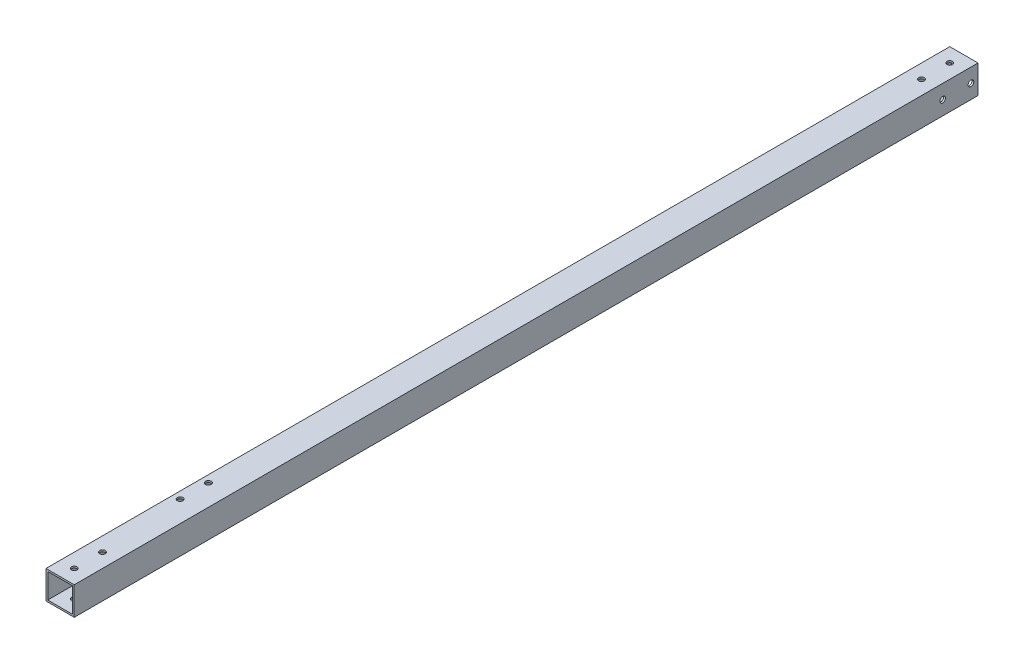
SolidWorks part; units mm, degrees
ref_plane "Front Plane" through (0, 0, 0) normal (0, 0, 1) x (1, 0, 0)
ref_plane "Top Plane" through (0, 0, 0) normal (0, 1, 0) x (1, 0, 0)
ref_plane "Right Plane" through (0, 0, 0) normal (1, 0, 0) x (0, 0, -1)
sketch "Sketch1" plane through (0, 0, 0) normal (0, 0, 1) x (1, 0, 0)
  line L1 (0, 0) -> (25.4, 0)
  line L2 (0, 0) -> (0, 25.4)
  line L3 (0, 25.4) -> (25.4, 25.4)
  line L4 (25.4, 0) -> (25.4, 25.4)
  line L5 (1.5875, 1.5875) -> (23.8125, 1.5875)
  line L6 (1.5875, 1.5875) -> (1.5875, 23.8125)
  line L7 (1.5875, 23.8125) -> (23.8125, 23.8125)
  line L8 (23.8125, 1.5875) -> (23.8125, 23.8125)
  dimension "D1" = 25.4
  dimension "D2" = 1.5875
  dimension "D3" = 1.5875
  dimension "D4" = 1.5875
  dimension "D5" = 1.5875
extrude "Boss-Extrude1" add sketch "Sketch1" along normal blind 812.8
sketch "Sketch3" plane through (0, 25.4, 0) normal (0, 1, 0) x (1, 0, 0)
  line L0 (0, -406.4) -> (25.4, -406.4) construction
  line L1 (25.4, -812.8) -> (25.4, 0) construction
  line L2 (25.4, 0) -> (0, 0) construction
  line L4 (0, -812.8) -> (0, 0) construction
  circle A1 centre (12.7, -12.7) radius 2.54
  circle A5 centre (12.7, -38.1) radius 2.54
  circle A12 centre (12.7, -774.7) radius 2.54
  circle A13 centre (12.7, -800.1) radius 2.54
  circle A14 centre (6.35, -698.5) radius 2.54
  circle A15 centre (6.35, -673.1) radius 2.54
  point P17 (0, 0)
  point P18 (0, 0)
  point P19 (0, 0)
  point P20 (0, 0)
  dimension "D3" = 76.2
  dimension "D1" = 5.08
  dimension "D2" = 6.35
  dimension "D4" = 12.7
  dimension "D7" = 25.4
  dimension "1" = 25.4
extrude "Cut-Extrude2" cut sketch "Sketch3" against normal through all
sketch "Sketch4" plane through (25.4, 0, 0) normal (1, 0, 0) x (0, 0, -1)
  line L2 (0, 0) -> (0, 25.4) construction
  line L3 (-812.8, 25.4) -> (0, 25.4) construction
  circle A1 centre (-6.35, 12.7) radius 2.54
  circle A2 centre (-31.75, 12.7) radius 2.54
  dimension "D3" = 6.35
  dimension "D1" = 5.08
  dimension "D2" = 25.4
  dimension "D4" = 12.7
extrude "Cut-Extrude3" cut sketch "Sketch4" against normal up to next
sketch "Sketch5" plane through (0, 0, 0) normal (-1, 0, 0) x (0, 0, 1)
  line L0 (0, 12.7) -> (812.8, 12.7) construction
  line L1 (0, 25.4) -> (0, 0) construction
  line L2 (812.8, 25.4) -> (812.8, 0) construction
  circle A0 centre (39.6875, 12.7) radius 2.54
  circle A1 centre (730.25, 12.7) radius 2.54
  circle A2 centre (755.65, 12.7) radius 2.54
  dimension "D1" = 5.08
  dimension "D2" = 39.6875
  dimension "D3" = 25.4
  dimension "D4" = 57.15
extrude "Cut-Extrude4" cut sketch "Sketch5" against normal up to next
